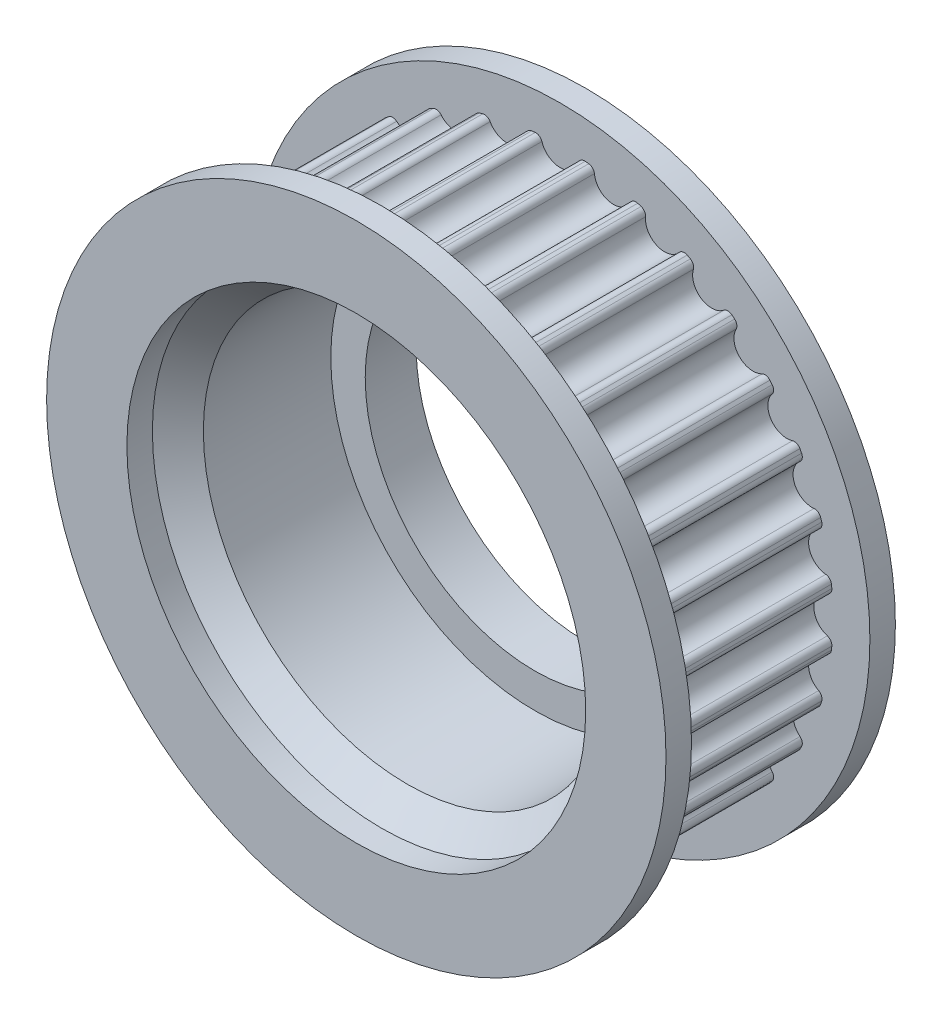
SolidWorks part; units mm, degrees
ref_plane "Plano frontal" through (0, 0, 0) normal (0, 0, 1) x (1, 0, 0)
ref_plane "Plano superior" through (0, 0, 0) normal (0, 1, 0) x (1, 0, 0)
ref_plane "Plano direito" through (0, 0, 0) normal (1, 0, 0) x (0, 0, -1)
sketch "Esboço1" plane through (0, 0, 0) normal (0, 0, 1) x (1, 0, 0)
  line L0 (0, 0) -> (0, -10.7) construction
  line L1 (2.0875, 10.4944) -> (1.9411, 9.7588) construction
  line L2 (0, 0) -> (-0.7495, -10.6737) construction
  line L3 (0, 0) -> (-2.8175, -10.3224) construction
  circle A0 centre (0, 0) radius 8
  arc A2 (0.7495, -10.6737) -> (-0.7495, -10.6737) centre (0, -10.7) ccw
  circle A3 centre (0, 0) radius 10.7 construction
  arc A4 (-1.3472, -10.6149) -> (-2.8175, -10.3224) centre (-2.0875, -10.4944) ccw
  arc A5 (-3.3922, -10.1481) -> (-4.7771, -9.5744) centre (-4.0947, -9.8855) ccw
  arc A6 (-5.3068, -9.2913) -> (-6.5532, -8.4584) centre (-5.9446, -8.8967) ccw
  arc A7 (-7.0175, -8.0775) -> (-8.0775, -7.0175) centre (-7.566, -7.566) ccw
  arc A8 (-8.4584, -6.5532) -> (-9.2913, -5.3068) centre (-8.8967, -5.9446) ccw
  arc A9 (-9.5744, -4.7771) -> (-10.1481, -3.3922) centre (-9.8855, -4.0947) ccw
  arc A10 (-10.3224, -2.8175) -> (-10.6149, -1.3472) centre (-10.4944, -2.0875) ccw
  arc A11 (-10.6737, -0.7495) -> (-10.6737, 0.7495) centre (-10.7, 0) ccw
  arc A12 (-10.6149, 1.3472) -> (-10.3224, 2.8175) centre (-10.4944, 2.0875) ccw
  arc A13 (-10.1481, 3.3922) -> (-9.5744, 4.7771) centre (-9.8855, 4.0947) ccw
  arc A14 (-9.2913, 5.3068) -> (-8.4584, 6.5532) centre (-8.8967, 5.9446) ccw
  arc A15 (-8.0775, 7.0175) -> (-7.0175, 8.0775) centre (-7.566, 7.566) ccw
  arc A16 (-6.5532, 8.4584) -> (-5.3068, 9.2913) centre (-5.9446, 8.8967) ccw
  arc A17 (-4.7771, 9.5744) -> (-3.3922, 10.1481) centre (-4.0947, 9.8855) ccw
  arc A18 (-2.8175, 10.3224) -> (-1.3472, 10.6149) centre (-2.0875, 10.4944) ccw
  arc A19 (-0.7495, 10.6737) -> (0.7495, 10.6737) centre (0, 10.7) ccw
  arc A20 (1.3472, 10.6149) -> (2.8175, 10.3224) centre (2.0875, 10.4944) ccw
  arc A21 (3.3922, 10.1481) -> (4.7771, 9.5744) centre (4.0947, 9.8855) ccw
  arc A22 (5.3068, 9.2913) -> (6.5532, 8.4584) centre (5.9446, 8.8967) ccw
  circle A68 centre (0, 0) radius 10.7
  arc A69 (7.0175, 8.0775) -> (8.0775, 7.0175) centre (7.566, 7.566) ccw
  arc A70 (8.4584, 6.5532) -> (9.2913, 5.3068) centre (8.8967, 5.9446) ccw
  arc A71 (9.5744, 4.7771) -> (10.1481, 3.3922) centre (9.8855, 4.0947) ccw
  arc A72 (10.3224, 2.8175) -> (10.6149, 1.3472) centre (10.4944, 2.0875) ccw
  arc A73 (10.6737, 0.7495) -> (10.6737, -0.7495) centre (10.7, 0) ccw
  arc A74 (10.6149, -1.3472) -> (10.3224, -2.8175) centre (10.4944, -2.0875) ccw
  arc A75 (10.1481, -3.3922) -> (9.5744, -4.7771) centre (9.8855, -4.0947) ccw
  arc A76 (9.2913, -5.3068) -> (8.4584, -6.5532) centre (8.8967, -5.9446) ccw
  arc A77 (8.0775, -7.0175) -> (7.0175, -8.0775) centre (7.566, -7.566) ccw
  arc A78 (6.5532, -8.4584) -> (5.3068, -9.2913) centre (5.9446, -8.8967) ccw
  arc A79 (4.7771, -9.5744) -> (3.3922, -10.1481) centre (4.0947, -9.8855) ccw
  arc A80 (2.8175, -10.3224) -> (1.3472, -10.6149) centre (2.0875, -10.4944) ccw
  point P144 (0, 0)
  dimension "D1" = 16
  dimension "D2" = 21.4
  dimension "D3" = 1.5
  dimension "D4" = 11.25
  dimension "D5" = 32
extrude "Ressalto-extrusão1" add sketch "Esboço1" along normal blind 7 contours A8 A68 A7 A6 A5 A4 A2 A22 A21 A20 A19 A18 A17 A16 A15 A14 A13 A12 A11 A10 A9 A0
fillet "Filete1" radius 0.25 64 edges at (-10.1481, 3.3922, 3.5) (-9.5744, 4.7771, 3.5) (-10.6149, 1.3472, 3.5) (-10.3224, 2.8175, 3.5) (-10.6737, -0.7495, 3.5) (-10.6737, 0.7495, 3.5) (-10.3224, -2.8175, 3.5) (-10.6149, -1.3472, 3.5) (-9.5744, -4.7771, 3.5) (-10.1481, -3.3922, 3.5) (-9.2913, 5.3068, 3.5) (-8.4584, 6.5532, 3.5) (-8.0775, 7.0175, 3.5) (-7.0175, 8.0775, 3.5) (-6.5532, 8.4584, 3.5) (-5.3068, 9.2913, 3.5) (-4.7771, 9.5744, 3.5) (-3.3922, 10.1481, 3.5) (-2.8175, 10.3224, 3.5) (-1.3472, 10.6149, 3.5) (-0.7495, 10.6737, 3.5) (0.7495, 10.6737, 3.5) (1.3472, 10.6149, 3.5) (2.8175, 10.3224, 3.5) (3.3922, 10.1481, 3.5) (4.7771, 9.5744, 3.5) (5.3068, 9.2913, 3.5) (6.5532, 8.4584, 3.5) (7.0175, 8.0775, 3.5) (8.0775, 7.0175, 3.5) (8.4584, 6.5532, 3.5) (9.2913, 5.3068, 3.5) (9.5744, 4.7771, 3.5) (10.1481, 3.3922, 3.5) (10.3224, 2.8175, 3.5) (10.6149, 1.3472, 3.5) (10.6737, 0.7495, 3.5) (10.6737, -0.7495, 3.5) (10.6149, -1.3472, 3.5) (10.3224, -2.8175, 3.5) (10.1481, -3.3922, 3.5) (9.5744, -4.7771, 3.5) (9.2913, -5.3068, 3.5) (8.4584, -6.5532, 3.5) (8.0775, -7.0175, 3.5) (7.0175, -8.0775, 3.5) (6.5532, -8.4584, 3.5) (5.3068, -9.2913, 3.5) (4.7771, -9.5744, 3.5) (3.3922, -10.1481, 3.5) (2.8175, -10.3224, 3.5) (1.3472, -10.6149, 3.5) (0.7495, -10.6737, 3.5) (-0.7495, -10.6737, 3.5) (-1.3472, -10.6149, 3.5) (-2.8175, -10.3224, 3.5) (-3.3922, -10.1481, 3.5) (-4.7771, -9.5744, 3.5) (-5.3068, -9.2913, 3.5) (-6.5532, -8.4584, 3.5) (-7.0175, -8.0775, 3.5) (-8.0775, -7.0175, 3.5) (-8.4584, -6.5532, 3.5) (-9.2913, -5.3068, 3.5)
chamfer "Chanfro1" distance 1 angle 45 1 edges at (8, 0, 7)
sketch "Esboço2" plane through (0, 0, 0) normal (0, 0, -1) x (-1, 0, 0)
  circle A0 centre (0, 0) radius 6.65
  circle A3 centre (0, 0) radius 8
  circle A4 centre (0, 0) radius 8 construction
  dimension "D1" = 13.3
extrude "Ressalto-extrusão2" add sketch "Esboço2" against normal blind 1
sketch "Esboço3" plane through (0, 0, 0) normal (0, 0, -1) x (-1, 0, 0)
  circle A0 centre (0, 0) radius 12.15
  circle A1 centre (0, 0) radius 6.65
  circle A2 centre (0, 0) radius 6.65 construction
  dimension "D1" = 5.5
extrude "Ressalto-extrusão3" add sketch "Esboço3" along normal blind 1
sketch "Esboço4" plane through (0, 0, 7) normal (0, 0, 1) x (1, 0, 0)
  circle A0 centre (0, 0) radius 9 construction
  circle A1 centre (0, 0) radius 9
  circle A2 centre (0, 0) radius 12.15
  circle A3 centre (0, 0) radius 12.15 construction
extrude "Ressalto-extrusão4" add sketch "Esboço4" along normal blind 1
